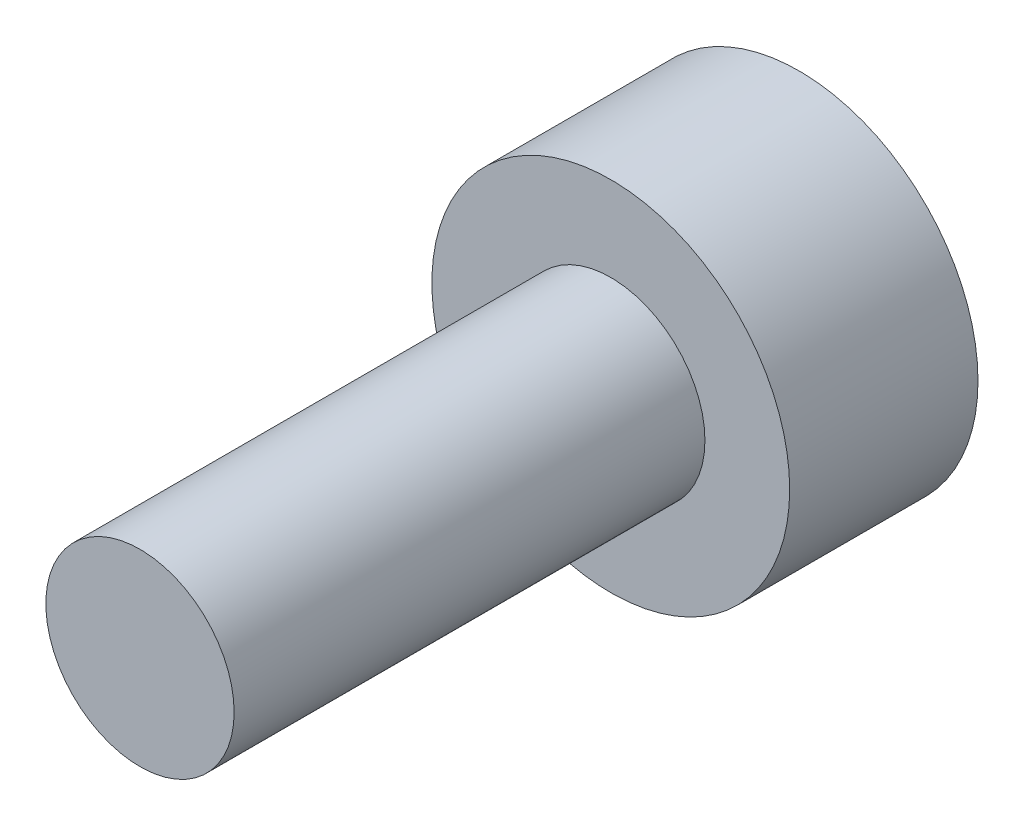
SolidWorks part; units mm, degrees
material "AISI 4340 Steel, normalized"
ref_plane "Front Plane" through (0, 0, 0) normal (0, 0, 1) x (1, 0, 0)
ref_plane "Top Plane" through (0, 0, 0) normal (0, 1, 0) x (1, 0, 0)
ref_plane "Right Plane" through (0, 0, 0) normal (1, 0, 0) x (0, 0, -1)
sketch "Sketch1" plane through (0, 0, 0) normal (0, 0, 1) x (1, 0, 0)
  circle A0 centre (0, 0) radius 1.9
extrude "Head_Envelope" add sketch "Sketch1" along normal blind 2 from offset 2
sketch "Sketch2" plane through (0, 0, 0) normal (0, 0, 1) x (1, 0, 0)
  circle A0 centre (0, 0) radius 1
extrude "Thread_Major_Envelope" add sketch "Sketch2" along normal blind 5
